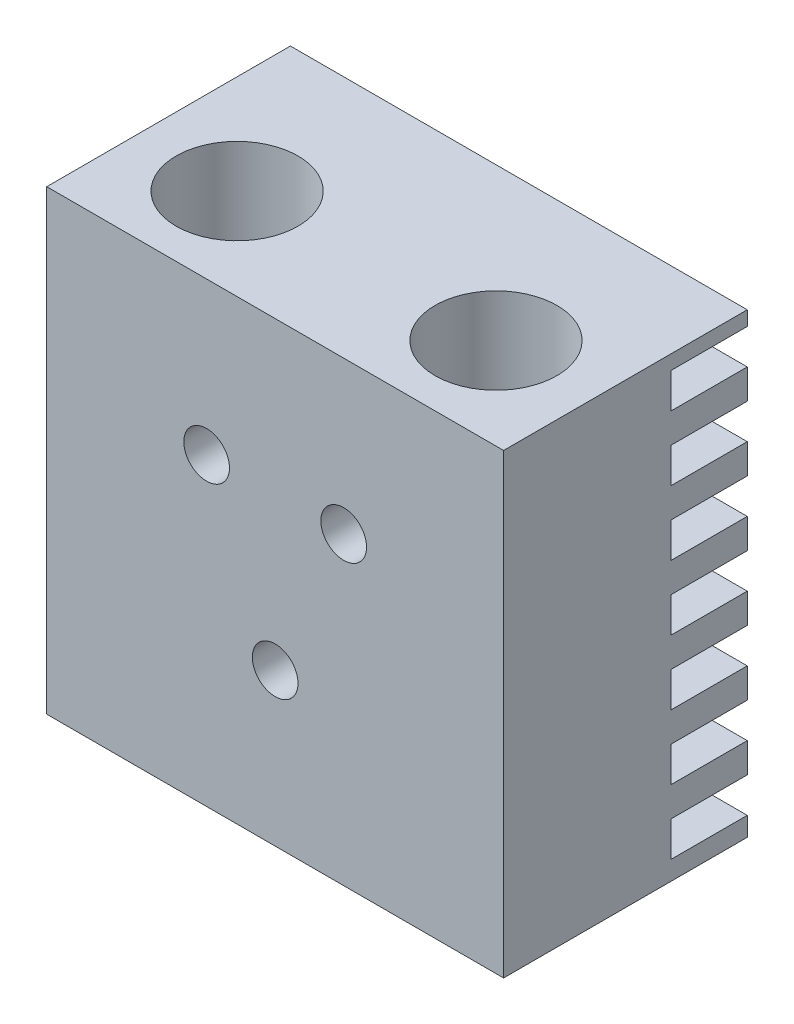
SolidWorks part; units mm, degrees
ref_plane "Front Plane" through (0, 0, 0) normal (0, 0, 1) x (1, 0, 0)
ref_plane "Top Plane" through (0, 0, 0) normal (0, 1, 0) x (1, 0, 0)
ref_plane "Right Plane" through (0, 0, 0) normal (1, 0, 0) x (0, 0, -1)
sketch "Sketch1" plane through (0, 0, 0) normal (0, 1, 0) x (1, 0, 0)
  line L1 (0, 0) -> (30, 0)
  line L2 (0, 0) -> (0, 16)
  line L3 (0, 16) -> (30, 16)
  line L4 (30, 0) -> (30, 16)
  dimension "D1" = 16
  dimension "D2" = 30
extrude "Boss-Extrude1" add sketch "Sketch1" along normal blind 30
sketch "Sketch2" plane through (0, 30, 0) normal (0, 1, 0) x (1, 0, 0)
  line L0 (0, 0) -> (30, 0) construction
  line L1 (30, 0) -> (30, 16) construction
  line L2 (0, 16) -> (0, 0) construction
  circle A0 centre (6.5, 6) radius 2.1
  circle A1 centre (23.5, 6) radius 2.1
  dimension "D1" = 4.2
  dimension "D2" = 4.2
  dimension "D3" = 6
  dimension "D4" = 6
  dimension "D5" = 6.5
  dimension "D6" = 6.5
extrude "Cut-Extrude1" cut sketch "Sketch2" against normal up to next
sketch "Sketch3" plane through (0, 30, 0) normal (0, 1, 0) x (1, 0, 0)
  circle A0 centre (6.5, 6) radius 4
  circle A1 centre (23.5, 6) radius 4
  dimension "D1" = 8
  dimension "D2" = 8
extrude "Cut-Extrude2" cut sketch "Sketch3" against normal blind 6.5
sketch "Sketch4" plane through (0, 0, 0) normal (0, -1, 0) x (1, 0, 0)
  circle A0 centre (6.5, -6) radius 3.5
  circle A1 centre (23.5, -6) radius 3.5
  dimension "D1" = 7
  dimension "D2" = 7
extrude "Cut-Extrude3" cut sketch "Sketch4" against normal blind 14
sketch "Sketch6" plane through (30, 0, 0) normal (1, 0, 0) x (0, 0, -1)
  line L1 (0, 0) -> (16, 0) construction
  line L2 (17.3744, 3.55) -> (11, 3.55)
  line L3 (17.3744, 3.55) -> (17.3744, 1.25)
  line L4 (17.3744, 1.25) -> (11, 1.25)
  line L6 (11, 3.55) -> (11, 1.25)
  line L7 (16, 30) -> (16, 0) construction
  line L8 (17.3744, 5.5) -> (11, 5.5)
  line L9 (11, 7.8) -> (11, 5.5)
  line L10 (17.3744, 7.8) -> (11, 7.8)
  line L11 (17.3744, 7.8) -> (17.3744, 5.5)
  line L12 (17.3744, 9.75) -> (11, 9.75)
  line L13 (11, 12.05) -> (11, 9.75)
  line L14 (17.3744, 12.05) -> (11, 12.05)
  line L15 (17.3744, 12.05) -> (17.3744, 9.75)
  line L16 (17.3744, 14) -> (11, 14)
  line L17 (11, 16.3) -> (11, 14)
  line L18 (17.3744, 16.3) -> (11, 16.3)
  line L19 (17.3744, 16.3) -> (17.3744, 14)
  line L20 (17.3744, 18.25) -> (11, 18.25)
  line L21 (11, 20.55) -> (11, 18.25)
  line L22 (17.3744, 20.55) -> (11, 20.55)
  line L23 (17.3744, 20.55) -> (17.3744, 18.25)
  line L24 (17.3744, 22.5) -> (11, 22.5)
  line L25 (11, 24.8) -> (11, 22.5)
  line L26 (17.3744, 24.8) -> (11, 24.8)
  line L27 (17.3744, 24.8) -> (17.3744, 22.5)
  line L28 (17.3744, 26.75) -> (11, 26.75)
  line L29 (11, 29.05) -> (11, 26.75)
  line L35 (17.3744, 29.05) -> (11, 29.05)
  line L36 (17.3744, 29.05) -> (17.3744, 26.75)
  dimension "D1" = 1.25
  dimension "D2" = 2.3
  dimension "D3" = 5
  dimension "D4" = 7
extrude "Cut-Extrude8" cut sketch "Sketch6" against normal through all
sketch "Sketch7" plane through (0, 0, 0) normal (0, 0, 1) x (1, 0, 0)
  line L0 (0, 30) -> (0, 0) construction
  line L1 (0, 0) -> (30, 0) construction
  circle A0 centre (15, 10) radius 1.5
  circle A1 centre (10.5, 20) radius 1.5
  circle A2 centre (19.5, 20) radius 1.5
  point P4 (15, 0)
  dimension "D1" = 3
  dimension "D4" = 3
  dimension "D5" = 3
  dimension "D2" = 15
  dimension "D3" = 10
  dimension "D6" = 20
  dimension "D7" = 20
  dimension "D8" = 10.5
  dimension "D9" = 19.5
extrude "Cut-Extrude9" cut sketch "Sketch7" against normal blind 8
